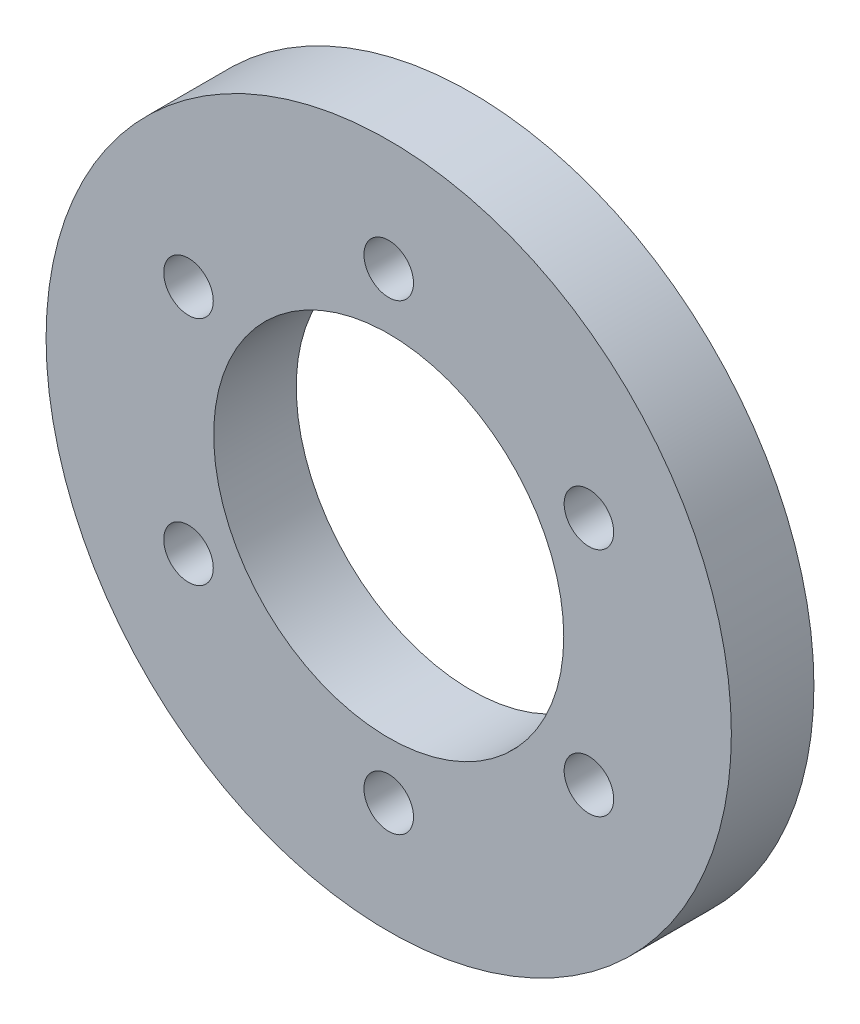
SolidWorks part; units mm, degrees
ref_plane "前视基准面" through (0, 0, 0) normal (0, 0, 1) x (1, 0, 0)
ref_plane "上视基准面" through (0, 0, 0) normal (0, 1, 0) x (1, 0, 0)
ref_plane "右视基准面" through (0, 0, 0) normal (1, 0, 0) x (0, 0, -1)
other "Configuration Table"
sketch "草图1" plane through (0, 0, 0) normal (0, 0, 1) x (1, 0, 0)
  circle A1 centre (0, 0) radius 20.75
  arc A4 (-12.1244, 5.5) -> (-12.1244, 8.5) centre (-12.1244, 7) ccw
  arc A5 (-12.1244, 8.5) -> (-12.1244, 5.5) centre (-12.1244, 7) ccw
  arc A6 (-12.1244, 5.5) -> (-12.1244, 8.5) centre (-12.1244, 7) ccw
  arc A7 (-12.1244, 8.5) -> (-12.1244, 5.5) centre (-12.1244, 7) ccw
  arc A8 (-12.1244, -8.5) -> (-12.1244, -5.5) centre (-12.1244, -7) ccw
  arc A9 (-12.1244, -5.5) -> (-12.1244, -8.5) centre (-12.1244, -7) ccw
  arc A10 (-12.1244, -8.5) -> (-12.1244, -5.5) centre (-12.1244, -7) ccw
  arc A11 (-12.1244, -5.5) -> (-12.1244, -8.5) centre (-12.1244, -7) ccw
  arc A12 (0, -15.5) -> (0, -12.5) centre (0, -14) ccw
  arc A13 (0, -12.5) -> (0, -15.5) centre (0, -14) ccw
  arc A14 (0, -15.5) -> (0, -12.5) centre (0, -14) ccw
  arc A15 (0, -12.5) -> (0, -15.5) centre (0, -14) ccw
  arc A16 (12.1244, -8.5) -> (12.1244, -5.5) centre (12.1244, -7) ccw
  arc A17 (12.1244, -5.5) -> (12.1244, -8.5) centre (12.1244, -7) ccw
  arc A18 (12.1244, -8.5) -> (12.1244, -5.5) centre (12.1244, -7) ccw
  arc A19 (12.1244, -5.5) -> (12.1244, -8.5) centre (12.1244, -7) ccw
  arc A20 (12.1244, 5.5) -> (12.1244, 8.5) centre (12.1244, 7) ccw
  arc A21 (12.1244, 8.5) -> (12.1244, 5.5) centre (12.1244, 7) ccw
  arc A22 (12.1244, 5.5) -> (12.1244, 8.5) centre (12.1244, 7) ccw
  arc A23 (12.1244, 8.5) -> (12.1244, 5.5) centre (12.1244, 7) ccw
  arc A24 (0, 12.5) -> (0, 15.5) centre (0, 14) ccw
  arc A25 (0, 15.5) -> (0, 12.5) centre (0, 14) ccw
  arc A26 (0, 12.5) -> (0, 15.5) centre (0, 14) ccw
  arc A27 (0, 15.5) -> (0, 12.5) centre (0, 14) ccw
  arc A29 (10.6, 0) -> (0, 10.6) centre (0, 0) ccw
  arc A30 (-10.6, 0) -> (10.6, 0) centre (0, 0) ccw
  arc A31 (0, 10.6) -> (-10.6, 0) centre (0, 0) ccw
  arc A32 (10.6, 0) -> (0, 10.6) centre (0, 0) ccw
  arc A33 (-10.6, 0) -> (10.6, 0) centre (0, 0) ccw
  arc A34 (0, 10.6) -> (-10.6, 0) centre (0, 0) ccw
  dimension "D1" = 41.5
  dimension "D3" = 0
  dimension "D4" = 0
  dimension "D5" = 0
  dimension "D6" = 0
  dimension "D7" = 0
  dimension "D8" = 0
  dimension "D9" = 0
extrude "凸台-拉伸1" add sketch "草图1" along normal blind 5
